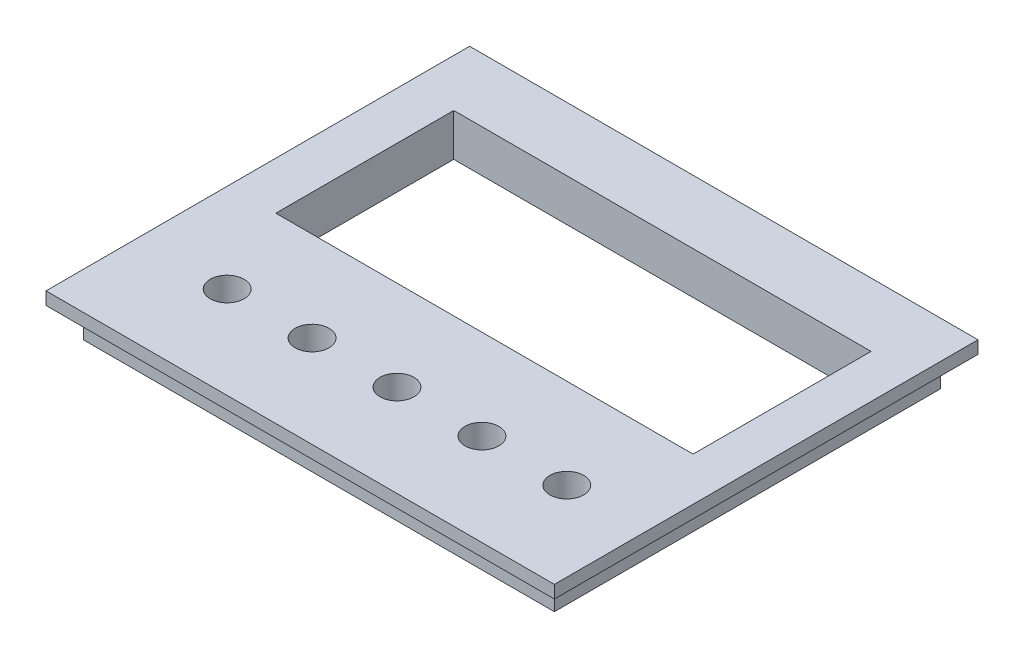
SolidWorks part; units mm, degrees
ref_plane "Front Plane" through (0, 0, 0) normal (0, 0, 1) x (1, 0, 0)
ref_plane "Top Plane" through (0, 0, 0) normal (0, 1, 0) x (1, 0, 0)
ref_plane "Right Plane" through (0, 0, 0) normal (1, 0, 0) x (0, 0, -1)
sketch "Sketch1" plane through (0, 0, 0) normal (0, 1, 0) x (1, 0, 0)
  line L1 (-59.6887, 52.0519) -> (60.3113, 52.0519)
  line L2 (-59.6887, 52.0519) -> (-59.6887, -47.9481)
  line L3 (-59.6887, -47.9481) -> (60.3113, -47.9481)
  line L4 (60.3113, 52.0519) -> (60.3113, -47.9481)
  dimension "D1" = 100
  dimension "D2" = 120
extrude "Boss-Extrude1" add sketch "Sketch1" along normal blind 10
sketch "Sketch2" plane through (0, 10, 0) normal (0, 1, 0) x (1, 0, 0)
  line L0 (60.3113, 52.0519) -> (-59.6887, 52.0519) construction
  line L1 (-48.4387, 37.0519) -> (50.0613, 37.0519)
  line L2 (-48.4387, 37.0519) -> (-48.4387, -4.9481)
  line L3 (-48.4387, -4.9481) -> (50.0613, -4.9481)
  line L4 (50.0613, 37.0519) -> (50.0613, -4.9481)
  line L5 (-59.6887, 52.0519) -> (-59.6887, -47.9481) construction
  dimension "D1" = 98.5
  dimension "D2" = 42
  dimension "D3" = 15
  dimension "D4" = 11.25
extrude "Cut-Extrude1" cut sketch "Sketch2" against normal blind 10
sketch "Sketch3" plane through (0, 0, 0) normal (0, -1, 0) x (1, 0, 0)
  line L0 (-59.6887, 47.9481) -> (60.3113, 47.9481) construction
  line L1 (-55.2887, 43.5481) -> (55.9113, 43.5481)
  line L2 (-55.2887, 43.5481) -> (-55.2887, -47.6519)
  line L3 (-55.2887, -47.6519) -> (55.9113, -47.6519)
  line L4 (55.9113, 43.5481) -> (55.9113, -47.6519)
  line L5 (-59.6887, -52.0519) -> (-59.6887, 47.9481) construction
  line L7 (60.3113, -52.0519) -> (-59.6887, -52.0519)
  line L8 (60.3113, -52.0519) -> (60.3113, 47.9481)
  line L9 (60.3113, 47.9481) -> (-59.6887, 47.9481)
  line L10 (-59.6887, -52.0519) -> (-59.6887, 47.9481)
  dimension "D1" = 4.4
  dimension "D2" = 4.4
  dimension "D3" = 4.4
  dimension "D4" = 4.4
extrude "Cut-Extrude3" cut sketch "Sketch3" against normal blind 7
sketch "Sketch4" plane through (0, 0, 0) normal (0, -1, 0) x (1, 0, 0)
  line L0 (-48.4387, 4.9481) -> (50.0613, 4.9481) construction
  line L1 (-48.1793, 41.9481) -> (-30.1793, 41.9481)
  line L2 (-48.1793, 41.9481) -> (-48.1793, 16.9481)
  line L3 (-48.1793, 16.9481) -> (-30.1793, 16.9481)
  line L4 (-30.1793, 41.9481) -> (-30.1793, 16.9481)
  line L5 (-28.1338, 41.9481) -> (-10.1338, 41.9481)
  line L6 (-28.1338, 41.9481) -> (-28.1338, 16.9481)
  line L7 (-28.1338, 16.9481) -> (-10.1338, 16.9481)
  line L8 (-10.1338, 41.9481) -> (-10.1338, 16.9481)
  line L9 (-8.0883, 41.9481) -> (9.9117, 41.9481)
  line L10 (-8.0883, 41.9481) -> (-8.0883, 16.9481)
  line L11 (-8.0883, 16.9481) -> (9.9117, 16.9481)
  line L12 (9.9117, 41.9481) -> (9.9117, 16.9481)
  line L13 (11.9573, 41.9481) -> (29.9573, 41.9481)
  line L14 (11.9573, 41.9481) -> (11.9573, 16.9481)
  line L15 (11.9573, 16.9481) -> (29.9573, 16.9481)
  line L16 (29.9573, 41.9481) -> (29.9573, 16.9481)
  line L17 (32.0028, 41.9481) -> (50.0028, 41.9481)
  line L18 (32.0028, 41.9481) -> (32.0028, 16.9481)
  line L19 (32.0028, 16.9481) -> (50.0028, 16.9481)
  line L20 (50.0028, 41.9481) -> (50.0028, 16.9481)
  line L21 (-48.1793, -19.4827) -> (-48.1793, 51.1477) construction
  line L23 (50.0028, -6.721) -> (50.0028, 58.8046) construction
  dimension "D1" = 18
  dimension "D2" = 25
  dimension "D3" = 12
  dimension "D5" = 0
  dimension "D6" = 0
  dimension "D4" = 5
extrude "Cut-Extrude4" cut sketch "Sketch4" against normal blind 4
sketch "Sketch5" plane through (0, 4, 0) normal (0, -1, 0) x (1, 0, 0)
  line L0 (50.0028, 41.9481) -> (32.0028, 41.9481) construction
  line L1 (32.0028, 16.9481) -> (35.0028, 16.9481)
  line L2 (32.0028, 16.9481) -> (32.0028, 41.9481)
  line L3 (32.0028, 41.9481) -> (35.0028, 41.9481)
  line L4 (35.0028, 16.9481) -> (35.0028, 41.9481)
  line L5 (11.9573, 16.9481) -> (14.9573, 16.9481)
  line L6 (11.9573, 16.9481) -> (11.9573, 41.9481)
  line L7 (11.9573, 41.9481) -> (14.9573, 41.9481)
  line L8 (14.9573, 16.9481) -> (14.9573, 41.9481)
  line L9 (-8.0883, 16.9481) -> (-5.0883, 16.9481)
  line L10 (-8.0883, 16.9481) -> (-8.0883, 41.9481)
  line L11 (-8.0883, 41.9481) -> (-5.0883, 41.9481)
  line L12 (-5.0883, 16.9481) -> (-5.0883, 41.9481)
  line L13 (-28.1338, 16.9481) -> (-25.1338, 16.9481)
  line L14 (-28.1338, 16.9481) -> (-28.1338, 41.9481)
  line L15 (-28.1338, 41.9481) -> (-25.1338, 41.9481)
  line L16 (-25.1338, 16.9481) -> (-25.1338, 41.9481)
  line L17 (-48.1793, 16.9481) -> (-45.1793, 16.9481)
  line L18 (-48.1793, 16.9481) -> (-48.1793, 41.9481)
  line L19 (-48.1793, 41.9481) -> (-45.1793, 41.9481)
  line L20 (-45.1793, 16.9481) -> (-45.1793, 41.9481)
  line L21 (-48.1793, 41.9481) -> (-48.1793, 16.9481) construction
  dimension "D1" = 3
  dimension "D3" = 0
  dimension "D2" = 5
extrude "Cut-Extrude6" cut sketch "Sketch5" against normal blind 2.5
sketch "Sketch6" plane through (0, 4, 0) normal (0, -1, 0) x (1, 0, 0)
  line L0 (35.0028, 16.9481) -> (50.0028, 16.9481) construction
  line L1 (50.0028, 16.9481) -> (50.0028, 41.9481) construction
  line L2 (-30.1793, 16.9481) -> (-30.1793, 41.9481) construction
  circle A0 centre (41.5028, 26.1981) radius 4
  circle A1 centre (21.4573, 26.1981) radius 4
  circle A2 centre (1.4117, 26.1981) radius 4
  circle A3 centre (-18.6338, 26.1981) radius 4
  circle A4 centre (-38.6793, 26.1981) radius 4
  dimension "D1" = 9.25
  dimension "D2" = 8.5
  dimension "D4" = 8.5
  dimension "D3" = 5
extrude "Cut-Extrude12" cut sketch "Sketch6" against normal through all
